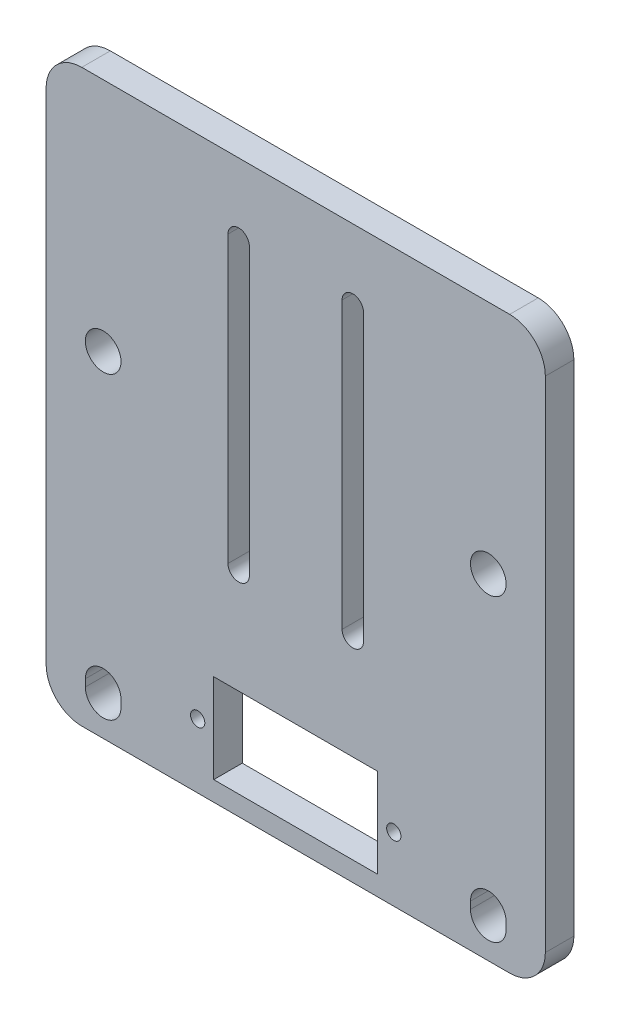
SolidWorks part; units mm, degrees
ref_plane "Front" through (0, 0, 0) normal (0, 0, 1) x (1, 0, 0)
ref_plane "Top" through (0, 0, 0) normal (0, 1, 0) x (1, 0, 0)
ref_plane "Right" through (0, 0, 0) normal (1, 0, 0) x (0, 0, -1)
sketch "Sketch4" plane through (0, 0, 0) normal (0, 0, 1) x (1, 0, 0)
  line L0 (-27, -34) -> (-27, -35) construction
  line L1 (-35, 40) -> (35, 40)
  line L2 (-35, 40) -> (-35, -40)
  line L3 (-35, -40) -> (35, -40)
  line L4 (35, 40) -> (35, -40)
  line L5 (-35, 40) -> (35, -40) construction
  line L6 (-35, -40) -> (35, 40) construction
  line L7 (-24.5, -34) -> (-24.5, -35)
  line L8 (-29.5, -34) -> (-29.5, -35)
  line L9 (0, -47.1607) -> (0, 39.6245) construction
  line L10 (27, -34) -> (27, -35) construction
  line L11 (24.5, -34) -> (24.5, -35)
  line L12 (29.5, -34) -> (29.5, -35)
  line L13 (-21.7344, 0) -> (13.0886, 0) construction
  line L14 (-15, 35) -> (15, 35) construction
  line L15 (-15, 35) -> (-15, -35) construction
  line L16 (-15, -35) -> (15, -35) construction
  line L17 (15, 35) -> (15, -35) construction
  line L18 (-15, 35) -> (15, -35) construction
  line L19 (-15, -35) -> (15, 35) construction
  circle A0 centre (-27, 7) radius 2.5
  arc A1 (-24.5, -34) -> (-29.5, -34) centre (-27, -34) ccw
  arc A2 (-29.5, -35) -> (-24.5, -35) centre (-27, -35) ccw
  arc A3 (24.5, -34) -> (29.5, -34) centre (27, -34) cw
  arc A4 (29.5, -35) -> (24.5, -35) centre (27, -35) cw
  circle A5 centre (27, 7) radius 2.5
  circle A6 centre (-15, 35) radius 1.5 construction
  circle A7 centre (15, 35) radius 1.5 construction
  circle A8 centre (15, -35) radius 1.5 construction
  circle A9 centre (-15, -35) radius 1.5 construction
  point P0 (0, 0)
  point P10 (-27, -34.5)
  point P19 (27, -34.5)
  point P28 (0, 0)
  dimension "D3" = 27
  dimension "D6" = 2.5
  dimension "D8" = 3
  dimension "D1" = 70
  dimension "D2" = 80
  dimension "D4" = 41
  dimension "D5" = 1
  dimension "D7" = 5
  dimension "D9" = 30
  dimension "D10" = 70
extrude "Boss-Extrude2" add sketch "Sketch4" along normal blind 4
fillet "Fillet1" radius 5 4 edges at (-35, -40, 2) (35, -40, 2) (35, 40, 2) (-35, 40, 2)
sketch "Sketch6" plane through (0, 0, 4) normal (0, 0, 1) x (1, 0, 0)
  line L0 (0, 33.6968) -> (0, -10.6348) construction
  line L14 (0, -16.7522) -> (0, -49.1079) construction
  line L17 (-17.0445, -31) -> (16.4221, -31) construction
  line L21 (-30, -40) -> (30, -40) construction
  line L22 (-11.5, -24.75) -> (11.5, -24.75)
  line L23 (-11.5, -24.75) -> (-11.5, -37.25)
  line L24 (-11.5, -37.25) -> (11.5, -37.25)
  line L25 (11.5, -24.75) -> (11.5, -37.25)
  line L26 (-11.5, -24.75) -> (11.5, -37.25) construction
  line L27 (-11.5, -37.25) -> (11.5, -24.75) construction
  line L29 (-8, 30) -> (-8, -10) construction
  line L30 (-6.5, 30) -> (-6.5, -10)
  line L31 (-9.5, 30) -> (-9.5, -10)
  line L32 (30, 40) -> (-30, 40) construction
  line L33 (8, 30) -> (8, -10) construction
  line L34 (6.5, 30) -> (6.5, -10)
  line L35 (9.5, 30) -> (9.5, -10)
  circle A28 centre (-13.75, -31) radius 1
  circle A29 centre (13.75, -31) radius 1
  arc A30 (-6.5, 30) -> (-9.5, 30) centre (-8, 30) ccw
  arc A31 (-9.5, -10) -> (-6.5, -10) centre (-8, -10) ccw
  arc A32 (6.5, 30) -> (9.5, 30) centre (8, 30) cw
  arc A33 (9.5, -10) -> (6.5, -10) centre (8, -10) cw
  point P6 (-8, 10)
  point P15 (8, 10)
  point P22 (0, -31)
  dimension "D2" = 40
  dimension "D4" = 1.5
  dimension "D5" = 8
  dimension "D7" = 12.5
  dimension "D3" = 30
  dimension "D6" = 23
  dimension "D8" = 2
  dimension "D9" = 13.75
  dimension "D10" = 9
extrude "Cut-Extrude1" cut sketch "Sketch6" against normal through all
